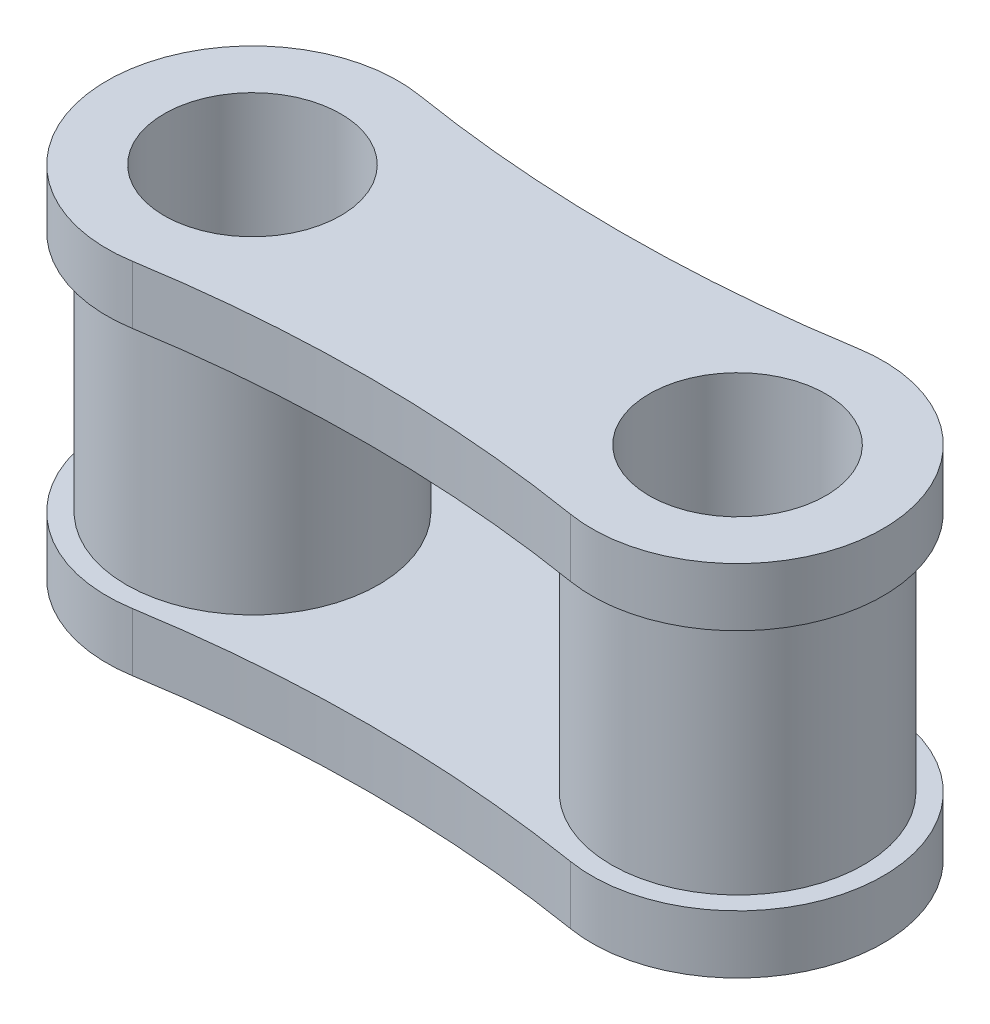
SolidWorks part; units mm, degrees
ref_plane "Front Plane" through (0, 0, 0) normal (0, 0, 1) x (1, 0, 0)
ref_plane "Top Plane" through (0, 0, 0) normal (0, 1, 0) x (1, 0, 0)
ref_plane "Right Plane" through (0, 0, 0) normal (1, 0, 0) x (0, 0, -1)
sketch "Sketch2" plane through (0, 0, 0) normal (0, 1, 0) x (1, 0, 0)
  line L0 (-3.175, 0) -> (3.175, 0) construction
  arc A0 (2.8677, -1.8801) -> (2.8677, 1.8801) centre (3.175, 0) ccw
  arc A1 (-2.8677, 1.8801) -> (-2.8677, -1.8801) centre (-3.175, 0) ccw
  arc A2 (-2.8677, 1.8801) -> (2.8677, 1.8801) centre (0, 19.4273) ccw
  arc A3 (2.8677, -1.8801) -> (-2.8677, -1.8801) centre (0, -19.4273) ccw
  point P2 (0, 0)
  dimension "D2" = 35.56
  dimension "D3" = 3.81
  dimension "D1" = 6.35
extrude "Boss-Extrude1" add sketch "Sketch2" along normal blind 0.762
sketch "Sketch3" plane through (0, 0.762, 0) normal (0, 1, 0) x (1, 0, 0)
  line L0 (-3.175, 0) -> (3.175, 0) construction
  circle A0 centre (-3.175, 0) radius 1.1557
  circle A1 centre (3.175, 0) radius 1.1557
  circle A2 centre (-3.175, 0) radius 1.651
  circle A3 centre (3.175, 0) radius 1.651
  point P2 (0, 0)
  dimension "D1" = 6.35
  dimension "D2" = 2.3114
  dimension "D3" = 3.302
extrude "Boss-Extrude2" add sketch "Sketch3" along normal blind 3.175
sketch "Sketch4" plane through (0, 3.937, 0) normal (0, 1, 0) x (1, 0, 0)
  arc A4 (2.8677, -1.8801) -> (-2.8677, -1.8801) centre (0, -19.4273) ccw
  arc A5 (2.8677, -1.8801) -> (2.8677, 1.8801) centre (3.175, 0) ccw
  arc A6 (-2.8677, 1.8801) -> (2.8677, 1.8801) centre (0, 19.4273) ccw
  arc A7 (-2.8677, 1.8801) -> (-2.8677, -1.8801) centre (-3.175, 0) ccw
  arc A8 (2.8677, -1.8801) -> (-2.8677, -1.8801) centre (0, -19.4273) ccw
  arc A9 (2.8677, -1.8801) -> (2.8677, 1.8801) centre (3.175, 0) ccw
  arc A10 (-2.8677, 1.8801) -> (2.8677, 1.8801) centre (0, 19.4273) ccw
  arc A11 (-2.8677, 1.8801) -> (-2.8677, -1.8801) centre (-3.175, 0) ccw
  dimension "D1" = 0
extrude "Boss-Extrude3" add sketch "Sketch4" along normal blind 0.762
sketch "Sketch5" plane through (0, 0.762, 0) normal (0, 1, 0) x (1, 0, 0)
  circle A0 centre (3.175, 0) radius 1.1557 construction
  circle A1 centre (-3.175, 0) radius 1.1557 construction
  circle A2 centre (3.175, 0) radius 1.1557
  circle A3 centre (-3.175, 0) radius 1.1557
extrude "Cut-Extrude1" cut sketch "Sketch5" against normal through all both and the other way through all
ref_plane "Mid Plane" through (0, 2.3495, 0) normal (0, 1, 0) x (1, 0, 0)
